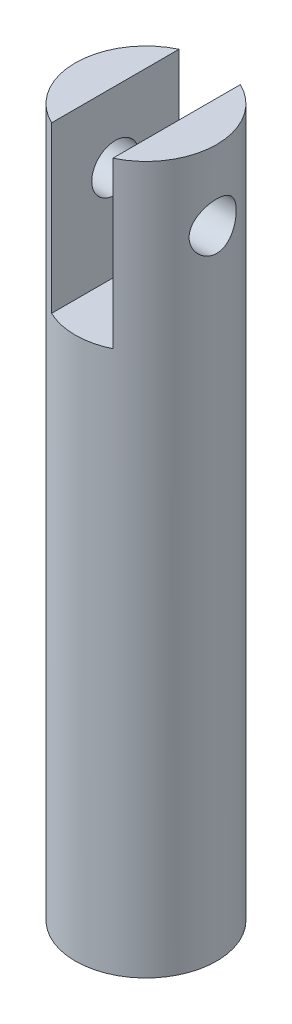
SolidWorks part; units mm, degrees
ref_plane "前视基准面" through (0, 0, 0) normal (0, 0, 1) x (1, 0, 0)
ref_plane "上视基准面" through (0, 0, 0) normal (0, 1, 0) x (1, 0, 0)
ref_plane "右视基准面" through (0, 0, 0) normal (1, 0, 0) x (0, 0, -1)
other "Configuration Table"
sketch "草图1" plane through (0, 0, 0) normal (0, 1, 0) x (1, 0, 0)
  circle A0 centre (0, 0) radius 3
  dimension "D1" = 6
extrude "凸台-拉伸1" add sketch "草图1" along normal blind 30 contours A0
sketch "草图2" plane through (0, 30, 0) normal (0, 1, 0) x (1, 0, 0)
  line L1 (-1.3, -3.1088) -> (1.3, -3.1088)
  line L2 (-1.3, -3.1088) -> (-1.3, 3.1088)
  line L3 (-1.3, 3.1088) -> (1.3, 3.1088)
  line L4 (1.3, -3.1088) -> (1.3, 3.1088)
  line L5 (-1.3, -3.1088) -> (1.3, 3.1088) construction
  line L6 (-1.3, 3.1088) -> (1.3, -3.1088) construction
  point P0 (0, 0)
  dimension "D1" = 2.6
extrude "切除-拉伸1" cut sketch "草图2" against normal blind 7
sketch "草图3" plane through (1.3, 0, 0) normal (-1, 0, 0) x (0, 0, 1)
  line L4 (2.7037, 30) -> (-2.7037, 30)
  line L5 (-2.7037, 30) -> (-2.7037, 23)
  line L6 (-2.7037, 23) -> (2.7037, 23)
  line L7 (2.7037, 23) -> (2.7037, 30)
  line L10 (-2.7037, 23) -> (2.7037, 23) construction
  circle A0 centre (0, 27) radius 1
  dimension "D1" = 0
  dimension "D2" = 4
  dimension "D3" = 2
extrude "切除-拉伸3" cut sketch "草图3" against normal through all both and the other way through all
